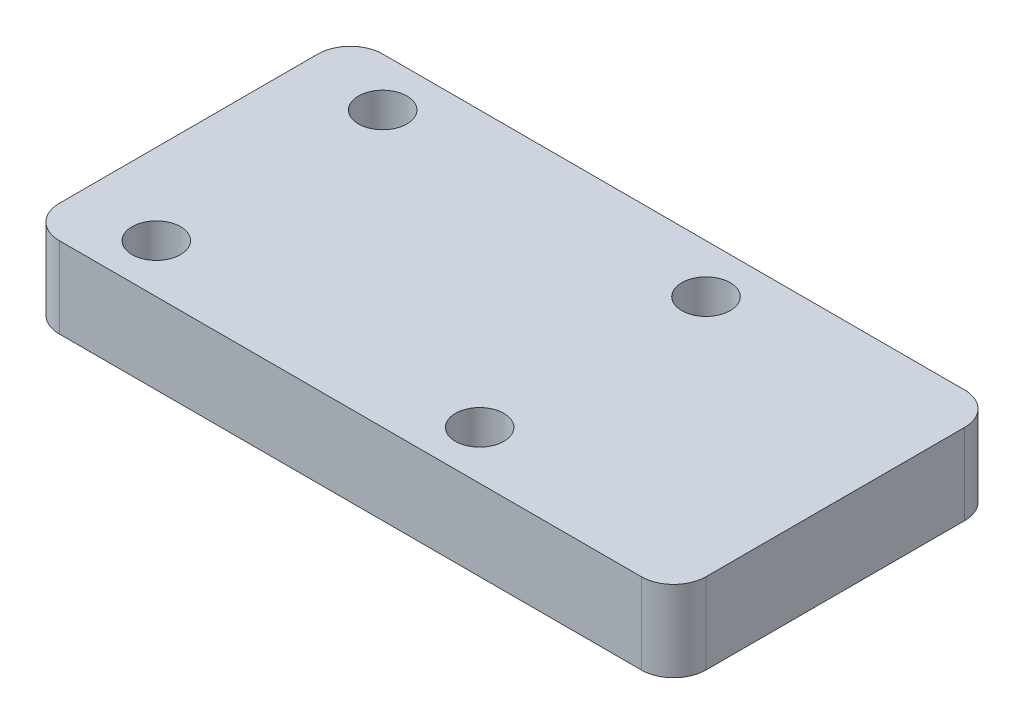
SolidWorks part; units mm, degrees
ref_plane "前视基准面" through (0, 0, 0) normal (0, 0, 1) x (1, 0, 0)
ref_plane "上视基准面" through (0, 0, 0) normal (0, 1, 0) x (1, 0, 0)
ref_plane "右视基准面" through (0, 0, 0) normal (1, 0, 0) x (0, 0, -1)
other "Configuration Table"
sketch "草图1" plane through (0, 0, 0) normal (0, 1, 0) x (1, 0, 0)
  line L0 (5, -7) -> (25, -7) construction
  line L1 (0, -10) -> (40, -10)
  line L2 (0, -10) -> (0, 10)
  line L3 (0, 10) -> (40, 10)
  line L4 (40, -10) -> (40, 10)
  line L5 (0, 0) -> (40, 0) construction
  circle A0 centre (5, -7) radius 1.5
  circle A1 centre (25, -7) radius 1.5
  circle A2 centre (25, 7) radius 1.5
  circle A3 centre (5, 7) radius 1.5
  point P10 (0, 0)
  dimension "D5" = 3
  dimension "D1" = 40
  dimension "D2" = 20
  dimension "D3" = 3
  dimension "D4" = 20
  dimension "D6" = 5
extrude "凸台-拉伸1" add sketch "草图1" along normal blind 5
fillet "圆角1" radius 2 4 edges at (0, 2.5, -10) (40, 2.5, -10) (0, 2.5, 10) (40, 2.5, 10)
